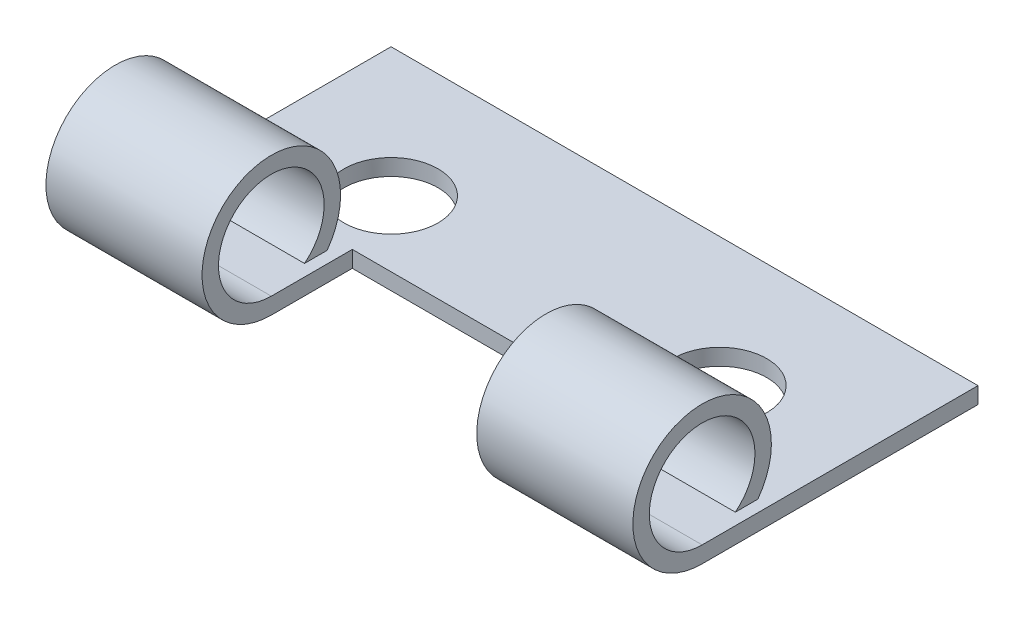
SolidWorks part; units mm, degrees
ref_plane "Alzado" through (0, 0, 0) normal (0, 0, 1) x (1, 0, 0)
ref_plane "Planta" through (0, 0, 0) normal (0, 1, 0) x (1, 0, 0)
ref_plane "Vista lateral" through (0, 0, 0) normal (1, 0, 0) x (0, 0, -1)
sketch "Croquis4" plane through (0, 0, 0) normal (1, 0, 0) x (0, 0, -1)
  line L0 (0, 0) -> (14, 0) construction
  line L1 (14, 0) -> (14, 0.7)
  line L2 (14, 0.7) -> (2.25, 0.7)
  line L3 (4.6249, 1.2) -> (3.6642, 1.2)
  line L4 (2.25, 0) -> (14, 0)
  arc A0 (3.6642, 1.2) -> (2.25, 0.7) centre (2.25, 2.95) ccw
  arc A1 (4.6249, 1.2) -> (2.25, 0) centre (2.25, 2.95) ccw
  circle A2 centre (2.25, 2.95) radius 2.95 construction
  circle A3 centre (2.25, 2.95) radius 2.25 construction
  point P8 (0, 2.95)
  dimension "D1" = 4.5
  dimension "D2" = 14
  dimension "D3" = 0.7
  dimension "D5" = 0.5
  dimension "D4" = 0.7
extrude "Saliente-Extruir1" add sketch "Croquis4" along normal mid plane 25
sketch "Croquis5" plane through (0, 0.7, 0) normal (0, 1, 0) x (1, 0, 0)
  line L0 (12.5, 14) -> (12.5, 2.25) construction
  line L1 (12.5, 14) -> (-12.5, 14) construction
  line L2 (0, 14) -> (0, 6.4236) construction
  circle A0 centre (7, 8.5) radius 2
  circle A1 centre (-7, 8.5) radius 2
  dimension "D1" = 4
  dimension "D2" = 5.5
  dimension "D3" = 5.5
  dimension "D4" = 14
extrude "Cortar-Extruir1" cut sketch "Croquis5" against normal up to next
sketch "Croquis6" plane through (0, 0.7, 0) normal (0, 1, 0) x (1, 0, 0)
  line L1 (-5.85, 5.7) -> (5.85, 5.7)
  line L2 (-5.85, 5.7) -> (-5.85, -0.7)
  line L3 (-5.85, -0.7) -> (5.85, -0.7)
  line L4 (5.85, 5.7) -> (5.85, -0.7)
  line L5 (-12.5, -0.7) -> (12.5, -0.7) construction
  line L6 (12.5, 5.2) -> (-12.5, 5.2) construction
  point P8 (0, -0.7)
  dimension "D1" = 0.5
  dimension "D2" = 11.7
extrude "Cortar-Extruir2" cut sketch "Croquis6" along normal through all both and the other way through all
